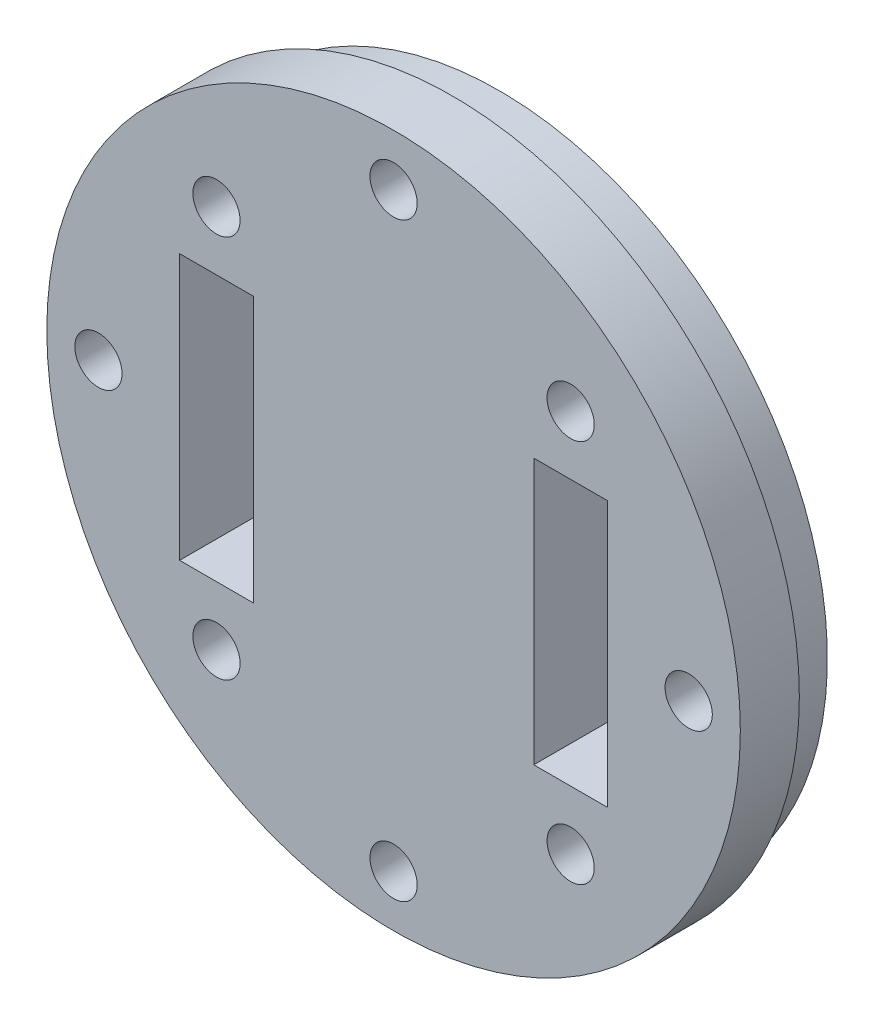
SolidWorks part; units mm, degrees
material "ABS"
ref_plane "正面" through (0, 0, 0) normal (0, 0, 1) x (1, 0, 0)
ref_plane "平面" through (0, 0, 0) normal (0, 1, 0) x (1, 0, 0)
ref_plane "右側面" through (0, 0, 0) normal (1, 0, 0) x (0, 0, -1)
sketch "ｽｹｯﾁ1" plane through (0, 0, 0) normal (0, 0, 1) x (1, 0, 0)
  circle A0 centre (0, 0) radius 23.5
  dimension "D1" = 47
extrude "ﾎﾞｽ - 押し出し1" add sketch "ｽｹｯﾁ1" along normal blind 4
sketch "ｽｹｯﾁ2" plane through (0, 0, 0) normal (0, 0, -1) x (-1, 0, 0)
  circle A0 centre (0, 0) radius 22.225
  dimension "D1" = 44.45
extrude "ﾎﾞｽ - 押し出し2" add sketch "ｽｹｯﾁ2" along normal blind 3.175
sketch "ｽｹｯﾁ3" plane through (0, 0, -3.175) normal (0, 0, -1) x (-1, 0, 0)
  circle A0 centre (0, 0) radius 20 construction
  circle A1 centre (0, 20) radius 1.6
  circle A2 centre (20, 0) radius 1.6
  circle A3 centre (0, -20) radius 1.6
  circle A4 centre (-20, 0) radius 1.6
  point P14 (0, 0)
  dimension "D1" = 40
  dimension "D2" = 3.2
  dimension "D3" = 4
extrude "ｶｯﾄ - 押し出し1" cut sketch "ｽｹｯﾁ3" against normal through all
sketch "ｽｹｯﾁ4" plane through (0, 0, -3.175) normal (0, 0, -1) x (-1, 0, 0)
  line L0 (0, 15.9237) -> (0, -13.2434) construction
  line L1 (-12, 0) -> (12, 0) construction
  line L2 (-9.5, -9) -> (-14.5, 9) construction
  line L3 (9.5, 9) -> (14.5, 9)
  line L4 (9.5, 9) -> (9.5, -9)
  line L5 (9.5, -9) -> (14.5, -9)
  line L6 (14.5, 9) -> (14.5, -9)
  line L7 (9.5, 9) -> (14.5, -9) construction
  line L8 (9.5, -9) -> (14.5, 9) construction
  line L9 (-9.5, 9) -> (-14.5, -9) construction
  line L10 (-14.5, 9) -> (-14.5, -9)
  line L11 (-9.5, -9) -> (-14.5, -9)
  line L12 (-9.5, 9) -> (-9.5, -9)
  line L13 (-9.5, 9) -> (-14.5, 9)
  point P14 (0, 0)
  dimension "D1" = 5
  dimension "D2" = 18
  dimension "D3" = 12
extrude "ｶｯﾄ - 押し出し2" cut sketch "ｽｹｯﾁ4" against normal through all
sketch "ｽｹｯﾁ5" plane through (0, 0, -3.175) normal (0, 0, -1) x (-1, 0, 0)
  line L0 (-12, -13.9536) -> (-12, 14.768) construction
  line L1 (0, 0) -> (0, 12.7509) construction
  line L2 (-9.5, 9) -> (-14.5, 9) construction
  line L3 (0, 0) -> (-12, 0) construction
  circle A0 centre (-12, 13) radius 1.6
  circle A1 centre (-12, -13) radius 1.6
  circle A2 centre (12, -13) radius 1.6
  circle A3 centre (12, 13) radius 1.6
  dimension "D2" = 3.2
  dimension "D1" = 12
  dimension "D3" = 4
extrude "ｶｯﾄ - 押し出し3" cut sketch "ｽｹｯﾁ5" against normal through all
